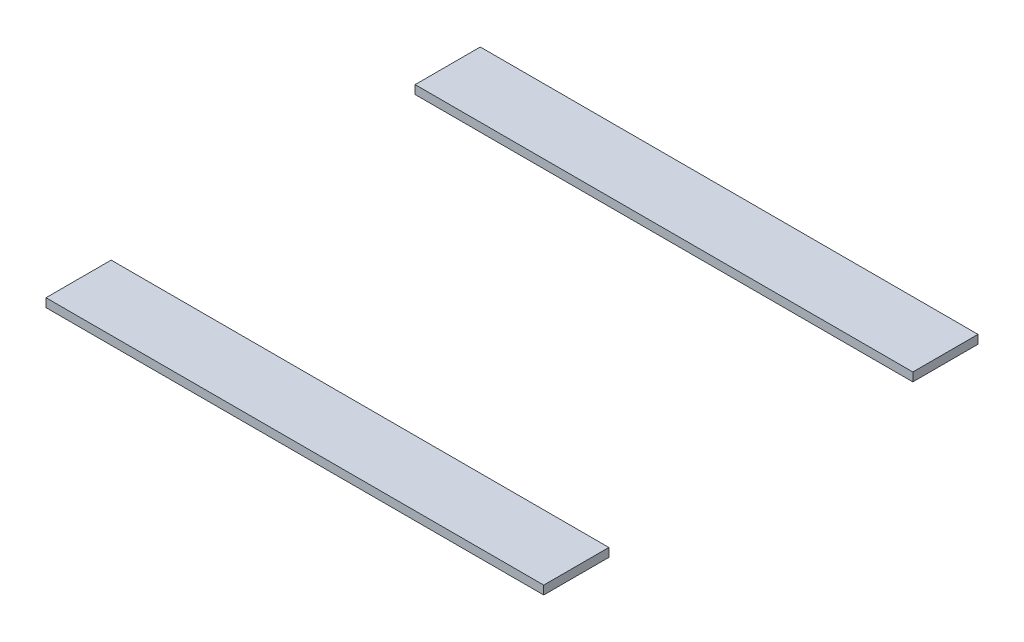
SolidWorks part; units mm, degrees
ref_plane "Front Plane" through (0, 0, 0) normal (0, 0, 1) x (1, 0, 0)
ref_plane "Top Plane" through (0, 0, 0) normal (0, 1, 0) x (1, 0, 0)
ref_plane "Right Plane" through (0, 0, 0) normal (1, 0, 0) x (0, 0, -1)
sketch "Sketch1" plane through (0, 0, 0) normal (0, 1, 0) x (1, 0, 0)
  line L0 (0, 0) -> (-35, 0) construction
  line L1 (0, 0) -> (0, -80.6396) construction
  line L2 (-80.6396, 80.6396) -> (104.2, 80.6396)
  line L3 (-80.6396, 80.6396) -> (-80.6396, -80.6396) construction
  line L4 (-80.6396, -80.6396) -> (104.2, -80.6396)
  line L5 (104.2, 80.6396) -> (104.2, -80.6396) construction
  line L6 (-80.6396, -76.4396) -> (104.2, -76.4396) construction
  line L7 (-80.6396, 76.4396) -> (104.2, 76.4396) construction
  line L8 (-146.4716, -76.4396) -> (-13.5925, -76.4396) construction
  line L9 (-80.6396, -77.4396) -> (104.2, -77.4396) construction
  line L10 (-80.6396, 77.4396) -> (104.2, 77.4396) construction
  line L11 (100, 80.6396) -> (100, -80.6396) construction
  line L12 (-80.6396, -56.4396) -> (104.2, -56.4396)
  line L13 (104.2, 56.4396) -> (-80.6396, 56.4396)
  line L14 (-3.5925, -56.4396) -> (-156.4716, -56.4396) construction
  line L15 (101, 80.6396) -> (101, -80.6396) construction
  line L16 (104.2, -80.6396) -> (104.2, -56.4396)
  line L17 (-80.6396, -56.4396) -> (-80.6396, -80.6396)
  line L18 (104.2, 80.6396) -> (104.2, 56.4396)
  line L19 (-80.6396, 56.4396) -> (-80.6396, 80.6396)
  line L20 (-80.6396, -80.6396) -> (-180.6396, -80.6396) construction
  line L21 (-180.6396, -80.6396) -> (-180.6396, 80.6396) construction
  line L22 (-180.6396, 80.6396) -> (-80.6396, 80.6396) construction
  line L23 (-80.6396, -103.9396) -> (80.6396, -103.9396) construction
  line L24 (80.6396, -103.9396) -> (80.6396, -80.6396) construction
  line L25 (-80.6396, -80.6396) -> (-80.6396, -103.9396) construction
  line L26 (-80.6396, -91.8396) -> (80.6396, -91.8396) construction
  line L27 (-77.4396, -103.9396) -> (-77.4396, 80.6396) construction
  line L28 (-76.4396, -103.9396) -> (-76.4396, 80.6396) construction
  line L29 (77.4396, -103.9396) -> (77.4396, 80.6396) construction
  line L30 (76.4396, 80.6396) -> (76.4396, -103.9396) construction
  line L31 (0, -80.6396) -> (0, -103.9396) construction
  line L32 (-80.6396, 80.6396) -> (-77.4396, 77.4396) construction
  line L33 (-77.4396, 77.4396) -> (-76.4396, 76.4396) construction
  line L34 (-76.4396, 76.4396) -> (0, 0) construction
  line L35 (-80.6396, -95.0396) -> (80.6396, -95.0396) construction
  line L36 (80.6396, -100.7396) -> (-80.6396, -100.7396) construction
  line L37 (-76.4396, -99.2396) -> (76.4396, -99.2396) construction
  line L38 (-76.4396, -100.2396) -> (76.4396, -100.2396) construction
  line L39 (76.4396, -96.0396) -> (-76.4396, -96.0396) construction
  circle A0 centre (0, 0) radius 35 construction
  circle A1 centre (0, 0) radius 35 construction
  dimension "D1" = 3.2
  dimension "D2" = 1
  dimension "D3" = 161.2791
  dimension "D4" = 100
  dimension "D5" = 1
  dimension "D6" = 3.2
  dimension "D7" = 3.2
  dimension "D8" = 100
  dimension "D9" = 11.2
  dimension "D10" = 3.2
  dimension "D11" = 1
  dimension "D12" = 0.5
  dimension "D13" = 1
  dimension "D14" = 3.2
extrude "Boss-Extrude1" add sketch "Sketch1" against normal up to vertex (3.2 mm away)
ref_plane "Plane1" through (0, 0, 80.6396) normal (0, 0, 1) x (1, 0, 0)
